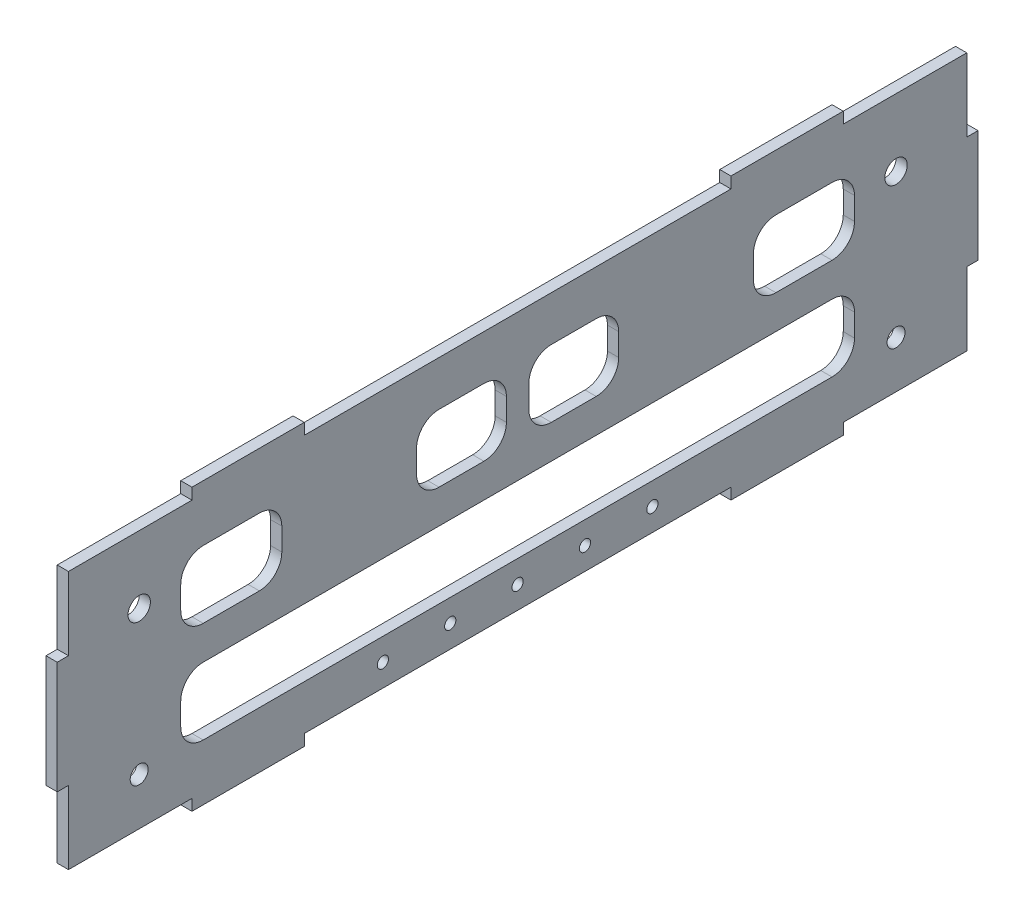
SolidWorks part; units mm, degrees
ref_plane "前视基准面" through (0, 0, 0) normal (0, 0, 1) x (1, 0, 0)
ref_plane "上视基准面" through (0, 0, 0) normal (0, 1, 0) x (1, 0, 0)
ref_plane "右视基准面" through (0, 0, 0) normal (1, 0, 0) x (0, 0, -1)
sketch "草图1" plane through (0, 0, 0) normal (1, 0, 0) x (0, 0, -1)
  line L0 (-400, 82.5) -> (-400, 115)
  line L1 (0, 0) -> (-55, 0)
  line L2 (0, 0) -> (0, 32.5)
  line L3 (0, 115) -> (-55, 115)
  line L4 (-400, 0) -> (-400, 32.5)
  line L5 (0, 82.5) -> (0, 115)
  line L6 (-345, 0) -> (-345, -5)
  line L7 (-345, -5) -> (-295, -5)
  line L8 (-295, 0) -> (-295, -5)
  line L9 (-345, 0) -> (-400, 0)
  line L10 (-105, 0) -> (-105, -5)
  line L11 (-105, -5) -> (-55, -5)
  line L12 (-55, 0) -> (-55, -5)
  line L13 (-105, 0) -> (-295, 0)
  line L14 (-105, 115) -> (-105, 120)
  line L15 (-105, 120) -> (-55, 120)
  line L16 (-55, 115) -> (-55, 120)
  line L17 (-105, 115) -> (-295, 115)
  line L18 (-295, 115) -> (-295, 120)
  line L19 (-295, 120) -> (-345, 120)
  line L20 (-345, 115) -> (-345, 120)
  line L21 (-400, 82.5) -> (-405, 82.5)
  line L22 (-345, 115) -> (-400, 115)
  line L23 (-400, 32.5) -> (-405, 32.5)
  line L24 (-405, 82.5) -> (-405, 32.5)
  line L25 (0, 82.5) -> (5, 82.5)
  line L26 (-31.5, 164.2766) -> (-31.5, -49.569) construction
  line L27 (0, 32.5) -> (5, 32.5)
  line L28 (5, 82.5) -> (5, 32.5)
  line L29 (-340, 50) -> (-60, 50)
  line L30 (-350, 40) -> (-350, 30)
  line L31 (-340, 20) -> (-60, 20)
  line L32 (-50, 40) -> (-50, 30)
  line L33 (-340, 95) -> (-315, 95)
  line L34 (-350, 85) -> (-350, 75)
  line L35 (-340, 65) -> (-315, 65)
  line L36 (-50, 85) -> (-50, 75)
  line L37 (-368.5, 146.6476) -> (-368.5, -49.569) construction
  line L38 (26.9442, 10) -> (-437.1038, 10) construction
  line L40 (-185, 65) -> (-165, 65)
  line L41 (-195, 85) -> (-195, 75)
  line L42 (-235, 65) -> (-215, 65)
  line L43 (-205, 85) -> (-205, 75)
  line L44 (-155, 85) -> (-155, 75)
  line L45 (-95, 85) -> (-95, 75)
  line L47 (-245, 85) -> (-245, 75)
  line L50 (-305, 85) -> (-305, 75)
  line L51 (-85, 95) -> (-60, 95)
  line L52 (-85, 65) -> (-60, 65)
  line L55 (-185, 95) -> (-165, 95)
  line L56 (-235, 95) -> (-215, 95)
  line L59 (-145, 95) -> (-145, 65) [skipped]
  line L60 (-105, 95) -> (-105, 65) [skipped]
  line L61 (-255, 95) -> (-255, 65) [skipped]
  line L62 (-295, 95) -> (-295, 65) [skipped]
  arc A0 (-60, 20) -> (-50, 30) centre (-60, 30) ccw
  arc A1 (-60, 50) -> (-50, 40) centre (-60, 40) cw
  arc A2 (-340, 50) -> (-350, 40) centre (-340, 40) ccw
  arc A3 (-350, 30) -> (-340, 20) centre (-340, 30) ccw
  arc A4 (-350, 75) -> (-340, 65) centre (-340, 75) ccw
  arc A5 (-340, 95) -> (-350, 85) centre (-340, 85) ccw
  arc A6 (-60, 65) -> (-50, 75) centre (-60, 75) ccw
  arc A7 (-60, 95) -> (-50, 85) centre (-60, 85) cw
  circle A8 centre (-368.5, 85) radius 5
  circle A9 centre (-368.5, 21) radius 4
  circle A10 centre (-31.5, 21) radius 4
  circle A11 centre (-31.5, 85) radius 5
  circle A12 centre (-200, 10) radius 2.5
  circle A13 centre (-170, 10) radius 2.5
  circle A14 centre (-140, 10) radius 2.5
  circle A15 centre (-230, 10) radius 2.5
  circle A16 centre (-260, 10) radius 2.5
  arc A17 (-305, 75) -> (-315, 65) centre (-315, 75) cw
  arc A18 (-305, 85) -> (-315, 95) centre (-315, 85) ccw
  arc A19 (-95, 75) -> (-85, 65) centre (-85, 75) ccw
  arc A20 (-95, 85) -> (-85, 95) centre (-85, 85) cw
  arc A21 (-195, 75) -> (-185, 65) centre (-185, 75) ccw
  arc A22 (-165, 65) -> (-155, 75) centre (-165, 75) ccw
  arc A23 (-215, 65) -> (-205, 75) centre (-215, 75) ccw
  arc A24 (-245, 75) -> (-235, 65) centre (-235, 75) ccw
  arc A25 (-245, 85) -> (-235, 95) centre (-235, 85) cw
  arc A26 (-215, 95) -> (-205, 85) centre (-215, 85) cw
  arc A27 (-185, 95) -> (-195, 85) centre (-185, 85) ccw
  arc A28 (-155, 85) -> (-165, 95) centre (-165, 85) ccw
  point P39 (-50, 20)
  point P42 (-50, 50)
  point P47 (-350, 20)
  point P52 (-350, 95)
  point P55 (-50, 65)
  point P58 (-50, 95)
  point P87 (-50, 80)
  point P126 (-195, 95)
  dimension "D29" = 10
  dimension "D32" = 10
  dimension "D33" = 10
  dimension "D34" = 8
  dimension "D35" = 8
  dimension "D41" = 5
  dimension "D46" = 10
  dimension "D47" = 10
  dimension "D1" = 400
  dimension "D2" = 115
  dimension "D3" = 5
  dimension "D4" = 5
  dimension "D5" = 5
  dimension "D6" = 5
  dimension "D7" = 5
  dimension "D8" = 5
  dimension "D9" = 50
  dimension "D10" = 50
  dimension "D11" = 50
  dimension "D12" = 50
  dimension "D13" = 50
  dimension "D14" = 50
  dimension "D15" = 55
  dimension "D16" = 55
  dimension "D17" = 55
  dimension "D18" = 55
  dimension "D19" = 32.5
  dimension "D20" = 32.5
  dimension "D21" = 300
  dimension "D22" = 300
  dimension "D23" = 30
  dimension "D24" = 30
  dimension "D25" = 50
  dimension "D26" = 50
  dimension "D27" = 20
  dimension "D28" = 20
  dimension "D30" = 31.5
  dimension "D31" = 31.5
  dimension "D36" = 30
  dimension "D37" = 30
  dimension "D38" = 21
  dimension "D39" = 21
  dimension "D40" = 10
  dimension "D42" = 10
  dimension "D43" = 145
  dimension "D44" = 3
  dimension "D45" = 3
extrude "凸台-拉伸1" add sketch "草图1" along normal blind 5
